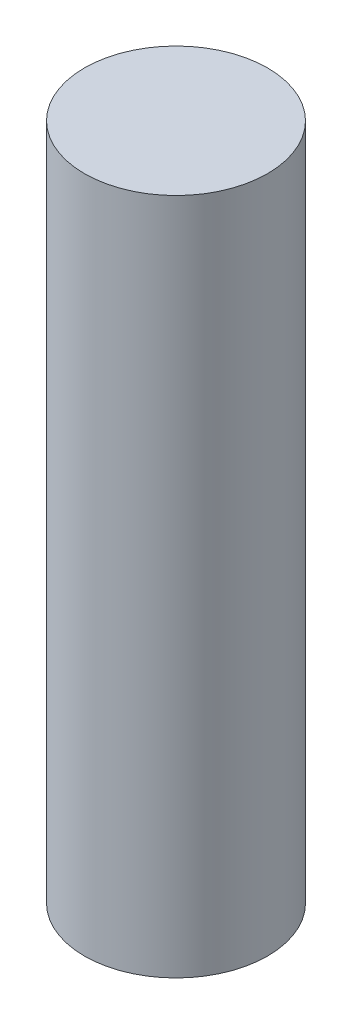
SolidWorks part; units mm, degrees
ref_plane "Front Plane" through (0, 0, 0) normal (0, 0, 1) x (1, 0, 0)
ref_plane "Top Plane" through (0, 0, 0) normal (0, 1, 0) x (1, 0, 0)
ref_plane "Right Plane" through (0, 0, 0) normal (1, 0, 0) x (0, 0, -1)
other "Configuration Table"
sketch "Sketch1" plane through (0, 0, 0) normal (0, 1, 0) x (1, 0, 0)
  circle A0 centre (0, 0) radius 12.7
  dimension "D1" = 25.4
extrude "Boss-Extrude1" add sketch "Sketch1" along normal blind 93.98
